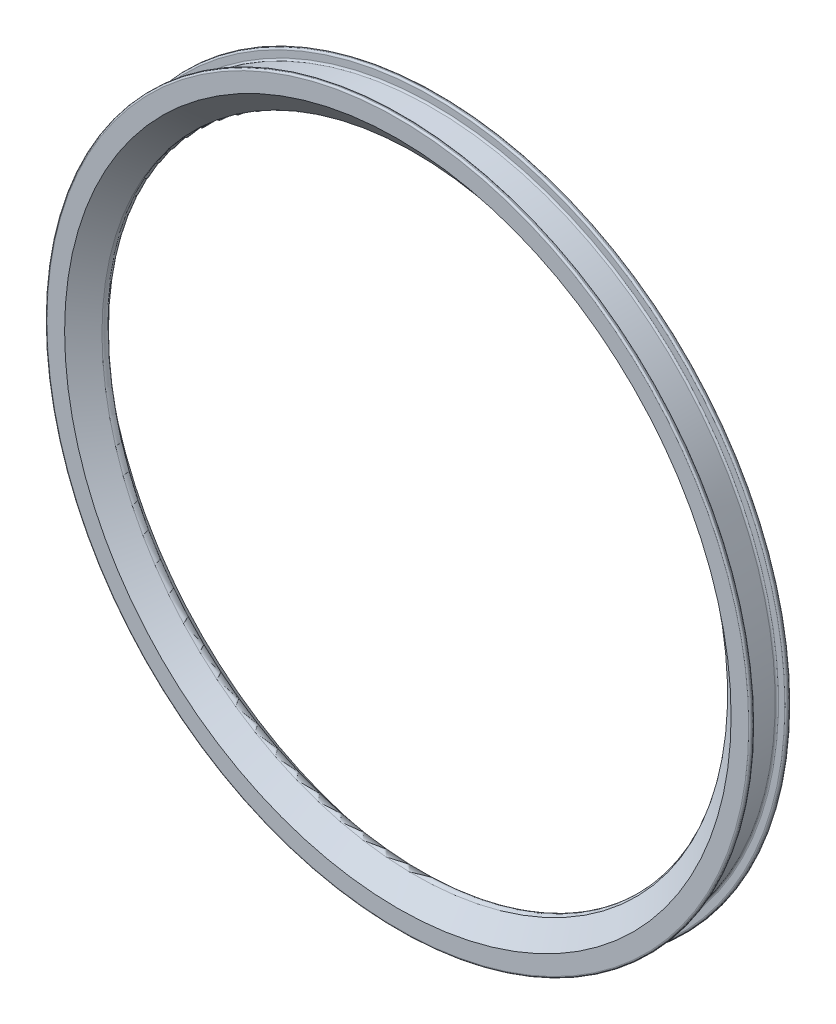
SolidWorks part; units mm, degrees
ref_plane "Front Plane" through (0, 0, 0) normal (0, 0, 1) x (1, 0, 0)
ref_plane "Top Plane" through (0, 0, 0) normal (0, 1, 0) x (1, 0, 0)
ref_plane "Right Plane" through (0, 0, 0) normal (1, 0, 0) x (0, 0, -1)
sketch "Sketch1" plane through (0, 0, 0) normal (0, 1, 0) x (1, 0, 0)
  line L0 (0, 28.4424) -> (0, -24.5989) construction
sketch "Sketch2" plane through (0, 0, 0) normal (0, 1, 0) x (1, 0, 0)
  line L0 (184, 0) -> (198.5, 12)
  line L1 (198.5, 12) -> (210, 12)
  line L2 (210, 12) -> (210, 9.5)
  line L3 (210, 9.5) -> (204.25, 9.5)
  line L4 (204.25, 9.5) -> (204.25, -9.5)
  line L5 (204.25, -9.5) -> (210, -9.5)
  line L6 (210, -9.5) -> (210, -12)
  line L7 (210, -12) -> (198.5, -12)
  line L8 (198.5, -12) -> (184, 0)
  line L9 (0, 0) -> (184, 0) construction
  point P10 (0, 0)
  point P12 (10.1253, 3.9284)
  dimension "D1" = 2.5
  dimension "D2" = 24
  dimension "D3" = 11.5
  dimension "D4" = 26
  dimension "D5" = 5.75
  dimension "D6" = 210
revolve "Revolve1" add sketch "Sketch2" angle 360 about L0
fillet "Fillet1" radius 2.5 1 edges at (-184, 0, 0)
fillet "Fillet2" radius 1 6 edges at (-210, 0, 12) (-210, 0, 9.5) (-210, 0, -9.5) (-210, 0, -12) (-204.25, 0, 9.5) (-204.25, 0, -9.5)
